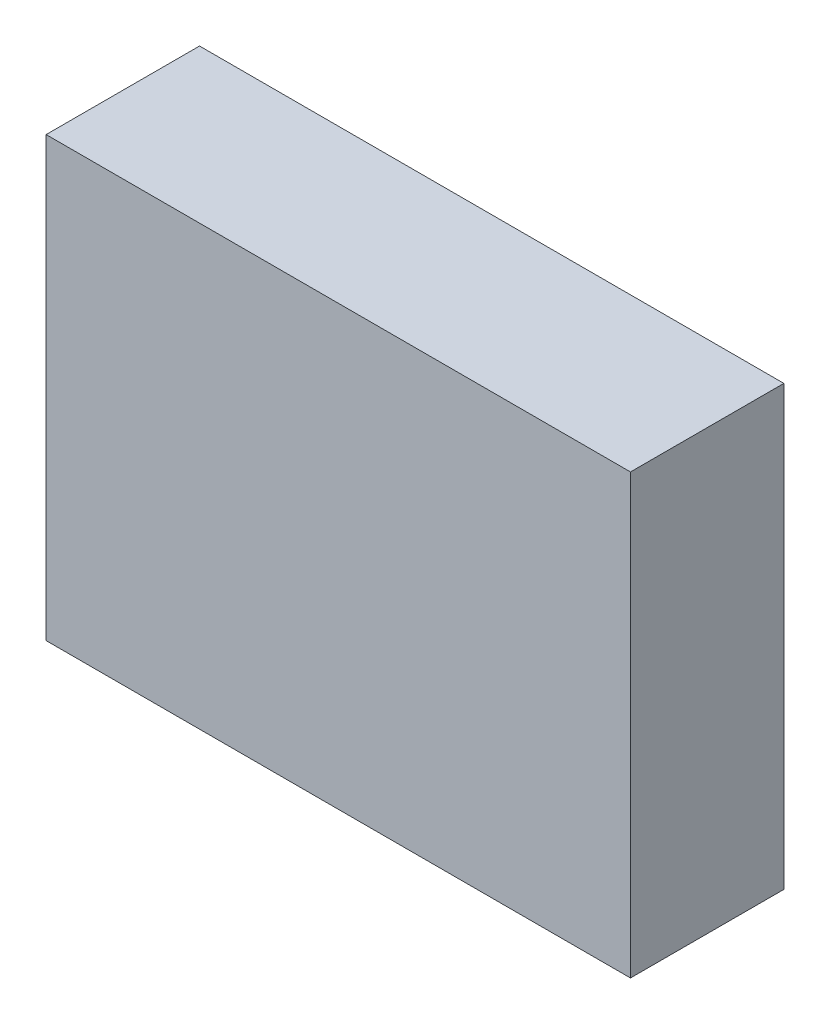
SolidWorks part; units mm, degrees
ref_plane "정면" through (0, 0, 0) normal (0, 0, 1) x (1, 0, 0)
ref_plane "윗면" through (0, 0, 0) normal (0, 1, 0) x (1, 0, 0)
ref_plane "우측면" through (0, 0, 0) normal (1, 0, 0) x (0, 0, -1)
sketch "스케치1" plane through (0, 0, 0) normal (0, 0, 1) x (1, 0, 0)
  line L1 (-40, 30) -> (40, 30)
  line L2 (-40, 30) -> (-40, -30)
  line L3 (-40, -30) -> (40, -30)
  line L4 (40, 30) -> (40, -30)
  line L5 (-40, 30) -> (40, -30) construction
  line L6 (-40, -30) -> (40, 30) construction
  point P0 (0, 0)
  dimension "D1" = 80
  dimension "D2" = 60
extrude "보스-돌출1" add sketch "스케치1" along normal blind 21
